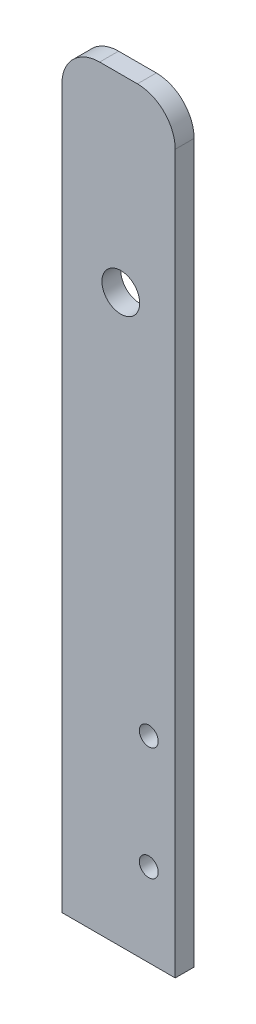
SolidWorks part; units mm, degrees
ref_plane "Front Plane" through (0, 0, 0) normal (0, 0, 1) x (1, 0, 0)
ref_plane "Top Plane" through (0, 0, 0) normal (0, 1, 0) x (1, 0, 0)
ref_plane "Right Plane" through (0, 0, 0) normal (1, 0, 0) x (0, 0, -1)
sketch "Sketch2" plane through (0, 0, 0) normal (0, 0, 1) x (1, 0, 0)
  line L1 (0, 254) -> (38.1, 254)
  line L2 (0, 254) -> (0, 0)
  line L3 (0, 0) -> (38.1, 0)
  line L4 (38.1, 254) -> (38.1, 0)
  dimension "D1" = 254
  dimension "D2" = 38.1
extrude "Boss-Extrude1" add sketch "Sketch2" along normal blind 6.35
fillet "Side Edge" radius 12.7 1 edges at (38.1, 254, 3.175)
fillet "Side Edge 2" radius 12.7 1 edges at (0, 254, 3.175)
sketch "Sketch4" plane through (0, 0, 6.35) normal (0, 0, 1) x (1, 0, 0)
  line L0 (38.1, 0) -> (38.1, 241.3) construction
  line L1 (0, 0) -> (38.1, 0) construction
  circle A0 centre (29.21, 27.94) radius 3.175
  circle A1 centre (29.21, 66.04) radius 3.175
  circle A2 centre (19.812, 190.5) radius 6.35
  dimension "D1" = 6.35
  dimension "D4" = 6.35
  dimension "D7" = 12.7
  dimension "D2" = 8.89
  dimension "D3" = 27.94
  dimension "D5" = 8.89
  dimension "D6" = 66.04
  dimension "D8" = 190.5
  dimension "D9" = 18.288
extrude "Cut-Extrude1" cut sketch "Sketch4" against normal through all
